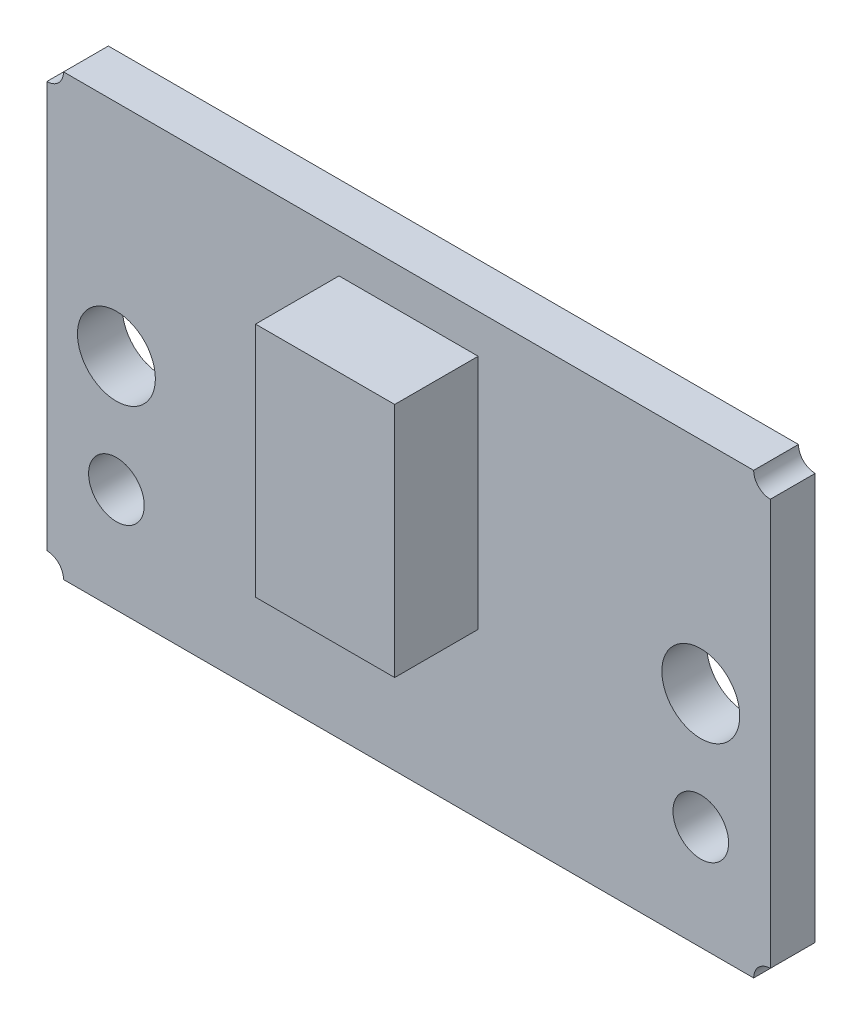
SolidWorks part; units mm, degrees
ref_plane "Front Plane" through (0, 0, 0) normal (0, 0, 1) x (1, 0, 0)
ref_plane "Top Plane" through (0, 0, 0) normal (0, 1, 0) x (1, 0, 0)
ref_plane "Right Plane" through (0, 0, 0) normal (1, 0, 0) x (0, 0, -1)
sketch "Sketch1" plane through (0, 0, 0) normal (0, 0, 1) x (1, 0, 0)
  line L1 (-13, 7.9) -> (13, 7.9)
  line L2 (-13, 7.9) -> (-13, -7.9)
  line L3 (-13, -7.9) -> (13, -7.9)
  line L4 (13, 7.9) -> (13, -7.9)
  line L5 (-13, 7.9) -> (13, -7.9) construction
  line L6 (-13, -7.9) -> (13, 7.9) construction
  point P0 (0, 0)
  dimension "D1" = 26
  dimension "D2" = 15.8
extrude "Boss-Extrude1" add sketch "Sketch1" along normal blind 1.61
sketch "Sketch2" plane through (0, 0, 1.61) normal (0, 0, 1) x (1, 0, 0)
  circle A0 centre (-13, 7.9) radius 0.6
  circle A1 centre (-13, -7.9) radius 0.6
  circle A2 centre (13, -7.9) radius 0.6
  circle A3 centre (13, 7.9) radius 0.6
  dimension "D1" = 1.2
extrude "Cut-Extrude1" cut sketch "Sketch2" against normal blind 1.61
sketch "Sketch3" plane through (0, 0, 1.61) normal (0, 0, 1) x (1, 0, 0)
  circle A0 centre (-10.5, 0) radius 1.4
  circle A1 centre (10.5, 0) radius 1.4
  circle A2 centre (-10.5, -4.15) radius 1
  circle A3 centre (10.5, -4.15) radius 1
  point P9 (0, 0)
  point P10 (0, 0)
  point P11 (0, 0)
  dimension "D1" = 2.8
  dimension "D2" = 10.5
  dimension "D4" = 2
  dimension "D5" = 4.15
  dimension "D3" = 10.5
extrude "Cut-Extrude2" cut sketch "Sketch3" against normal blind 11.61
sketch "Sketch4" plane through (0, 0, 1.61) normal (0, 0, 1) x (1, 0, 0)
  line L6 (-2.5, 6.5) -> (2.5, 6.5)
  line L7 (-2.5, 6.5) -> (-2.5, -2)
  line L8 (-2.5, -2) -> (2.5, -2)
  line L9 (2.5, 6.5) -> (2.5, -2)
  line L10 (-2.5, 6.5) -> (2.5, -2) construction
  line L11 (-2.5, -2) -> (2.5, 6.5) construction
  line L12 (12.4, 7.9) -> (-12.4, 7.9) construction
  point P0 (0, 2.25)
  point P5 (0, 0)
  dimension "D1" = 8.5
  dimension "D2" = 5
  dimension "D3" = 9.9
extrude "Boss-Extrude2" add sketch "Sketch4" along normal blind 3
